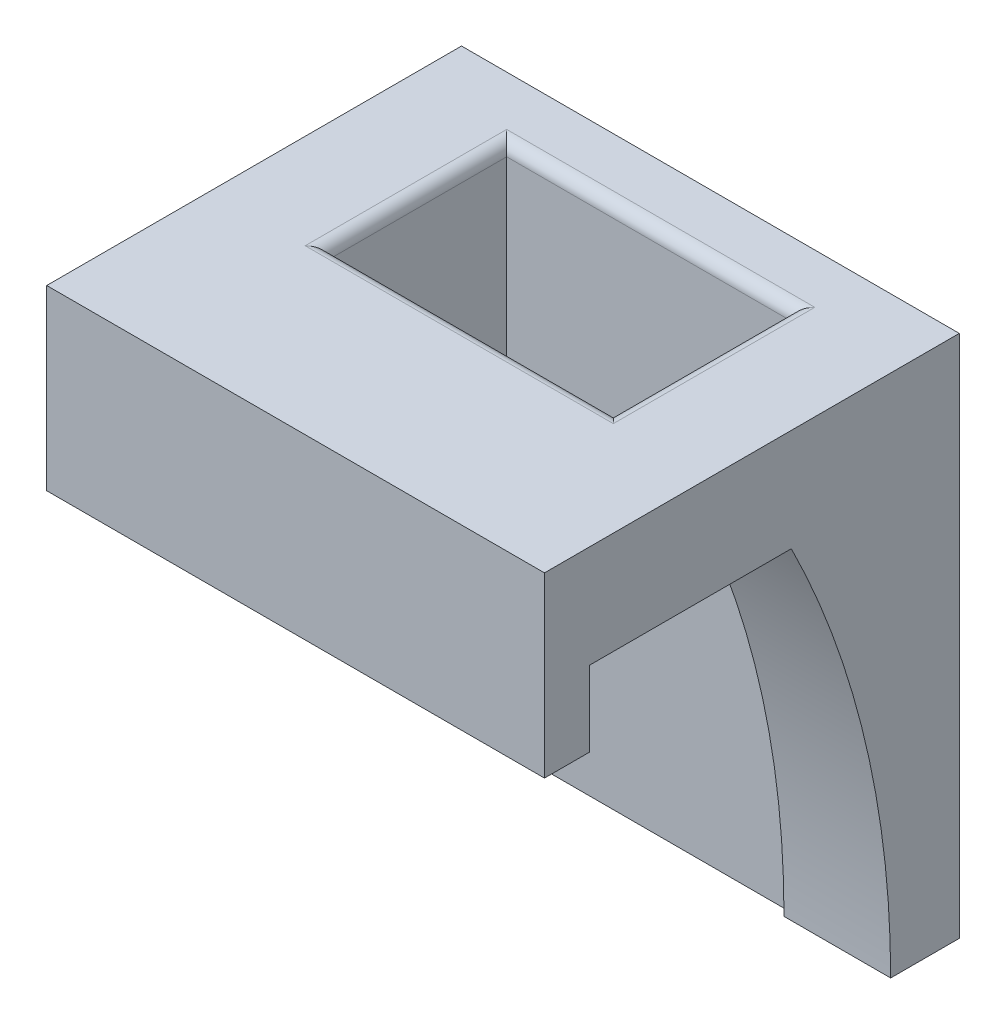
SolidWorks part; units mm, degrees
ref_plane "Front Plane" through (0, 0, 0) normal (0, 0, 1) x (1, 0, 0)
ref_plane "Top Plane" through (0, 0, 0) normal (0, 1, 0) x (1, 0, 0)
ref_plane "Right Plane" through (0, 0, 0) normal (1, 0, 0) x (0, 0, -1)
sketch "Sketch2" plane through (0, 0, 0) normal (1, 0, 0) x (0, 0, -1)
  line L1 (25.4, -35.56) -> (0, -35.56) construction
  line L6 (0, 0) -> (0, -6.35)
  line L7 (0, -6.35) -> (-3.81, -6.35)
  line L8 (-3.81, -6.35) -> (-3.81, 8.65)
  line L11 (0, 0) -> (17.018, 0)
  line L12 (-3.81, 8.65) -> (31.19, 8.65)
  line L13 (31.19, 8.65) -> (31.19, -35.56)
  line L14 (31.19, -35.56) -> (25.4, -35.56)
  arc A0 (25.4, -35.56) -> (17.018, 0) centre (-54.2213, -35.56) ccw
  dimension "D1" = 17.018
  dimension "D2" = 35.56
  dimension "D3" = 8.382
  dimension "D4" = 3.81
  dimension "D6" = 6.35
  dimension "D7" = 15
  dimension "D8" = 35
extrude "Boss-Extrude1" add sketch "Sketch2" along normal mid plane 42
ref_plane "Plane1" through (0, 8.65, 0) normal (0, 1, 0) x (1, 0, 0)
sketch "Sketch3" plane through (0, 8.65, 0) normal (0, 1, 0) x (1, 0, 0)
  line L1 (-12, 26) -> (12, 26)
  line L2 (-12, 26) -> (-12, 11)
  line L3 (-12, 11) -> (12, 11)
  line L4 (12, 26) -> (12, 11)
  dimension "D1" = 24
  dimension "D2" = 12
  dimension "D3" = 15
  dimension "D4" = 26
extrude "Cut-Extrude1" cut sketch "Sketch3" against normal through all
fillet "Fillet1" radius 1 4 edges at (0, 8.65, -11) (12, 8.65, -18.5) (0, 8.65, -26) (-12, 8.65, -18.5)
equation "\"D2@Sketch3\"=\"D1@Sketch3\"/2"
